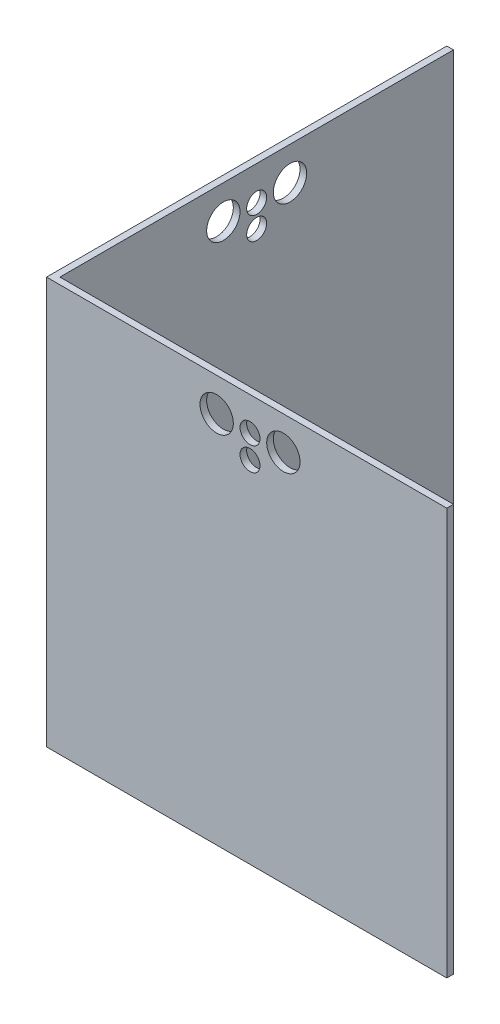
SolidWorks part; units mm, degrees
ref_plane "前视基准面" through (0, 0, 0) normal (0, 0, 1) x (1, 0, 0)
ref_plane "上视基准面" through (0, 0, 0) normal (0, 1, 0) x (1, 0, 0)
ref_plane "右视基准面" through (0, 0, 0) normal (1, 0, 0) x (0, 0, -1)
other "Configuration Table"
sketch "草图1" plane through (0, 0, 0) normal (0, 1, 0) x (1, 0, 0)
  line L0 (-71.6451, 99.5855) -> (-71.6451, -20.4145)
  line L1 (-71.6451, -20.4145) -> (48.3549, -20.4145)
  line L2 (48.3549, -20.4145) -> (48.3549, -18.4145)
  line L5 (-69.6451, 99.5855) -> (-19.4839, 49.4244)
  line L6 (-71.6451, 99.5855) -> (-69.6451, 99.5855)
  line L7 (-1.8063, 31.7467) -> (48.3549, -18.4145)
  arc A0 (-19.4839, 49.4244) -> (-1.8063, 31.7467) centre (-10.6451, 40.5855) ccw
extrude "凸台-拉伸1" add sketch "草图1" along normal blind 2
sketch "草图2" plane through (0, 2, 0) normal (0, 1, 0) x (1, 0, 0)
  line L0 (-69.6451, 99.5855) -> (-69.6451, -18.4145)
  line L1 (-69.6451, -18.4145) -> (48.3549, -18.4145)
  line L2 (48.3549, -18.4145) -> (48.3549, -20.4145)
  line L3 (48.3549, -20.4145) -> (-71.6451, -20.4145)
  line L4 (-71.6451, -20.4145) -> (-71.6451, 99.5855)
  line L5 (-69.6451, 99.5855) -> (-71.6451, 99.5855) construction
  line L6 (-71.6451, 99.5855) -> (-71.6451, -20.4145) construction
  line L7 (-71.6451, 99.5855) -> (-69.6451, 99.5855)
extrude "凸台-拉伸2" add sketch "草图2" along normal blind 120
sketch "草图3" plane through (0, 0, 18.4145) normal (0, 0, -1) x (-1, 0, 0)
  circle A1 centre (0.6451, 112) radius 5
  circle A2 centre (20.6451, 112) radius 5
  circle A5 centre (10.6451, 112) radius 3
extrude "切除-拉伸1" cut sketch "草图3" against normal blind 2
sketch "草图4" plane through (-69.6451, 0, 0) normal (1, 0, 0) x (0, 0, -1)
  circle A5 centre (30.5855, 112) radius 5
  circle A6 centre (50.5855, 112) radius 5
  circle A8 centre (40.5855, 111.7854) radius 3
  circle A9 centre (40.5855, 104.9921) radius 3
extrude "切除-拉伸2" cut sketch "草图4" against normal blind 2
sketch "草图5" plane through (0, 0, 18.4145) normal (0, 0, -1) x (-1, 0, 0)
  circle A0 centre (10.6451, 105) radius 3
extrude "切除-拉伸3" cut sketch "草图5" against normal blind 2
